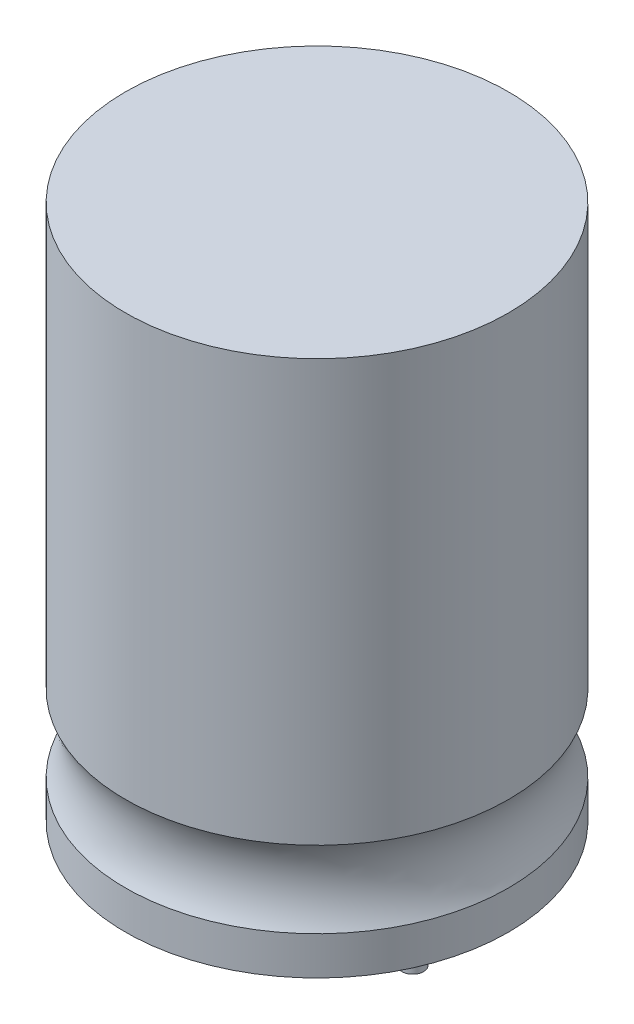
SolidWorks part; units mm, degrees
ref_plane "Front Plane" through (0, 0, 0) normal (0, 0, 1) x (1, 0, 0)
ref_plane "Top Plane" through (0, 0, 0) normal (0, 1, 0) x (1, 0, 0)
ref_plane "Right Plane" through (0, 0, 0) normal (1, 0, 0) x (0, 0, -1)
sketch "Sketch1" plane through (0, 0, 0) normal (0, 0, 1) x (1, 0, 0)
  line L0 (0, 14) -> (0, 0)
  line L1 (0, 0) -> (5, 0)
  line L2 (5, 0) -> (5, 1)
  line L3 (0, 14) -> (5, 14)
  line L4 (5, 14) -> (5, 3)
  arc A0 (5, 3) -> (5, 1) centre (6.7321, 2) ccw
  dimension "D3" = 2
  dimension "D1" = 5
  dimension "D2" = 14
  dimension "D4" = 1
  dimension "D5" = 3
revolve "Revolve1" add sketch "Sketch1" angle 360 about L0
sketch "Sketch2" plane through (0, 0, 0) normal (0, -1, 0) x (1, 0, 0)
  line L0 (-5, 0) -> (5, 0) construction
  circle A0 centre (0, 0) radius 5 construction
  circle A1 centre (2.5, 0) radius 0.2829
  circle A2 centre (-2.5, 0) radius 0.2829
  dimension "D1" = 5
  dimension "D2" = 2.5
extrude "Boss-Extrude1" add sketch "Sketch2" along normal blind 2
